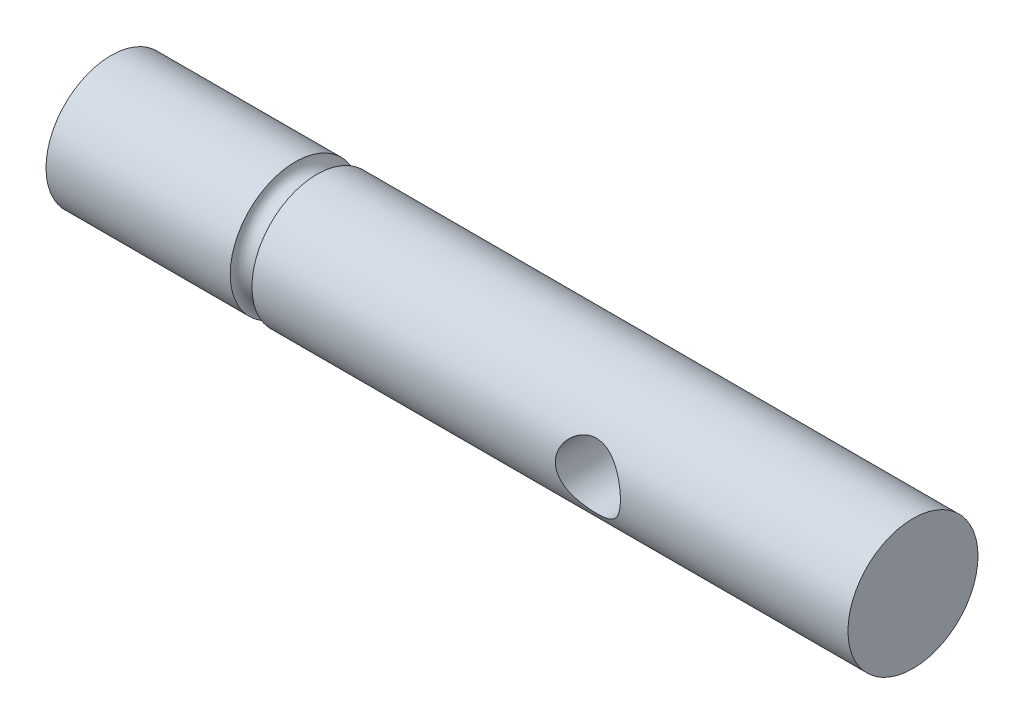
SolidWorks part; units mm, degrees
ref_plane "Front Plane" through (0, 0, 0) normal (1, 0, 0) x (0, 1, 0)
ref_plane "Top Plane" through (0, 0, 0) normal (0, 0, 1) x (0, 1, 0)
ref_plane "Right Plane" through (0, 0, 0) normal (0, 1, 0) x (-1, 0, 0)
sketch "Sketch1" plane through (0, 0, 0) normal (1, 0, 0) x (0, 1, 0)
  circle A0 centre (0, 0) radius 3
  dimension "D1" = 6
extrude "Boss-Extrude1" add sketch "Sketch1" along normal mid plane 37
sketch "Sketch2" plane through (0, 0, 0) normal (0, 0, 1) x (0, 1, 0)
  line L1 (-3, -18.5) -> (3, -18.5) construction
  circle A0 centre (0, -6.5) radius 1.5
  dimension "D1" = 3
  dimension "D4" = 12
extrude "Cut-Extrude1" cut sketch "Sketch2" against normal through all both and the other way through all
ref_plane "Plane2" through (0, 0, 0) normal (0, 0.866, -0.5) x (-1, 0, 0)
ref_plane "Plane3" through (-9.5, 0, 0) normal (-1, 0, 0) x (0, -1, 0)
sketch "Sketch3" plane through (-9.5, 0, 0) normal (-1, 0, 0) x (0, -1, 0)
  circle A0 centre (0, 0) radius 3 construction
  circle A1 centre (0, 0) radius 3
sweep "Cut-Sweep1" cut path "Sketch3" circular profile diameter 1 parameters "D3"=1
